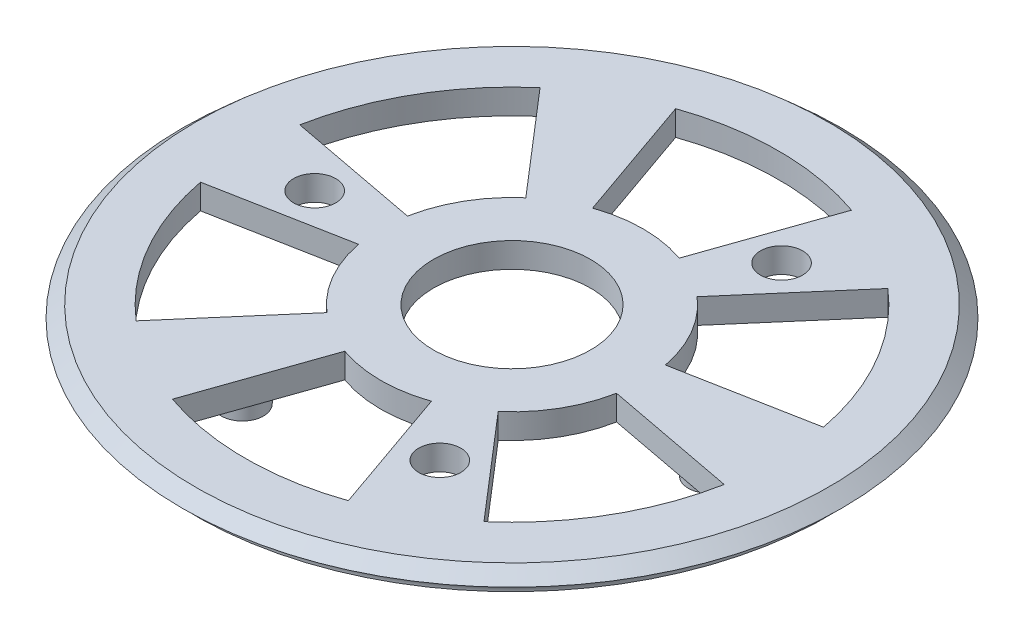
SolidWorks part; units mm, degrees
ref_plane "Front Plane" through (0, 0, 0) normal (0, 0, 1) x (1, 0, 0)
ref_plane "Top Plane" through (0, 0, 0) normal (0, 1, 0) x (1, 0, 0)
ref_plane "Right Plane" through (0, 0, 0) normal (1, 0, 0) x (0, 0, -1)
sketch "Sketch1" plane through (0, 0, 0) normal (0, 0, 1) x (1, 0, 0)
  line L0 (-3, 0) -> (3, 0)
  line L1 (-3, -3) -> (0, -3)
  line L2 (-3, -3) -> (-3, 3)
  line L3 (-3, 3) -> (0, 3)
  line L5 (-35.1, 18.9165) -> (-35.1, -17.1911)
  line L6 (0, 3) -> (3, 3)
  line L8 (4.5875, -1.5875) -> (0, -3)
  line L9 (4.5875, 1.5875) -> (3, 3)
  arc A0 (4.5875, 1.5875) -> (4.5875, -1.5875) centre (4.5875, 0) ccw
  point P0 (0, 0)
  dimension "D1" = 6
  dimension "D2" = 38.1
revolve "Revolve1" add sketch "Sketch1" angle 360 about L5
sketch "Sketch2" plane through (0, 3, 0) normal (0, 1, 0) x (1, 0, 0)
  line L12 (-45.4174, 11.9811) -> (-56.0464, 24.324)
  line L13 (-50.6347, 2.9446) -> (-66.6384, 5.9781)
  line L14 (-50.6347, -2.9446) -> (-66.6384, -5.9781)
  line L15 (-45.4174, -11.9811) -> (-56.0464, -24.324)
  line L16 (-40.3172, -14.9257) -> (-45.692, -30.3021)
  line L17 (-29.8828, -14.9257) -> (-24.508, -30.3021)
  line L18 (-24.7826, -11.9811) -> (-14.1536, -24.324)
  line L19 (-19.5653, -2.9446) -> (-3.5616, -5.9781)
  line L20 (-19.5653, 2.9446) -> (-3.5616, 5.9781)
  line L21 (-24.7826, 11.9811) -> (-14.1536, 24.324)
  line L22 (-29.8828, 14.9257) -> (-24.508, 30.3021)
  line L23 (-40.3172, 14.9257) -> (-45.692, 30.3021)
  circle A0 centre (-35.1, 0) radius 9.4613
  arc A2 (-45.4174, 11.9811) -> (-50.6347, 2.9446) centre (-35.1, 0) ccw
  circle A3 centre (-35.1, 0) radius 32.1 construction
  arc A4 (-50.6347, -2.9446) -> (-45.4174, -11.9811) centre (-35.1, 0) ccw
  arc A5 (-40.3172, -14.9257) -> (-29.8828, -14.9257) centre (-35.1, 0) ccw
  arc A6 (-24.7826, -11.9811) -> (-19.5653, -2.9446) centre (-35.1, 0) ccw
  arc A7 (-19.5653, 2.9446) -> (-24.7826, 11.9811) centre (-35.1, 0) ccw
  arc A8 (-29.8828, 14.9257) -> (-40.3172, 14.9257) centre (-35.1, 0) ccw
  arc A9 (-66.6384, 5.9781) -> (-66.6384, -5.9781) centre (-35.1, 0) ccw
  arc A10 (-56.0464, -24.324) -> (-45.692, -30.3021) centre (-35.1, 0) ccw
  arc A11 (-24.508, -30.3021) -> (-14.1536, -24.324) centre (-35.1, 0) ccw
  arc A12 (-3.5616, -5.9781) -> (-3.5616, 5.9781) centre (-35.1, 0) ccw
  arc A13 (-14.1536, 24.324) -> (-24.508, 30.3021) centre (-35.1, 0) ccw
  arc A14 (-45.692, 30.3021) -> (-56.0464, 24.324) centre (-35.1, 0) ccw
  dimension "D1" = 6.35
extrude "Boss-Extrude1" add sketch "Sketch2" against normal up to surface (3 mm away) up to face at (-73.2, 0, 0)
sketch "Sketch3" plane through (0, 3, 0) normal (0, 1, 0) x (1, 0, 0)
  circle A2 centre (-46.9838, 20.5834) radius 2.54
  circle A4 centre (-11.3323, 0) radius 2.54
  circle A6 centre (-46.9838, -20.5834) radius 2.54
sketch "Sketch4" plane through (0, 3, 0) normal (0, 1, 0) x (1, 0, 0)
  circle A1 centre (-23.2162, 20.5834) radius 2.54
  circle A3 centre (-23.2162, -20.5834) radius 2.54
  circle A4 centre (-58.8677, 0) radius 2.54
  dimension "D1" = 3
extrude "Boss-Extrude2" add sketch "Sketch3" against normal blind 6
extrude "Cut-Extrude1" cut sketch "Sketch4" against normal up to surface (3 mm away) up to face at (-49.5238, 0, 20.5834)
